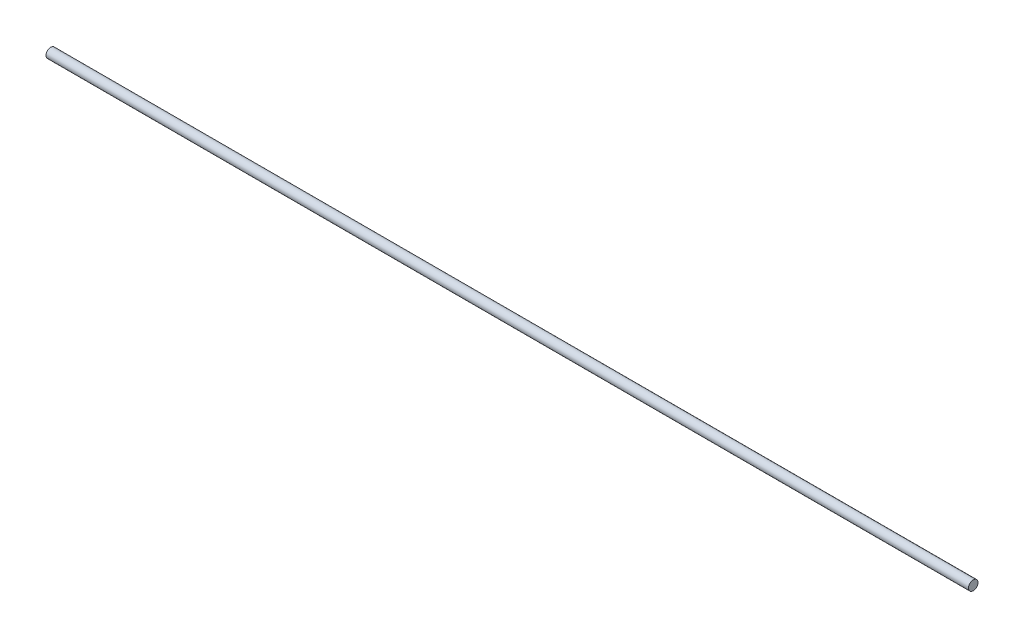
SolidWorks part; units mm, degrees
material "Alloy Steel"
ref_plane "Front Plane" through (0, 0, 0) normal (0, 0, 1) x (1, 0, 0)
ref_plane "Top Plane" through (0, 0, 0) normal (0, 1, 0) x (1, 0, 0)
ref_plane "Right Plane" through (0, 0, 0) normal (1, 0, 0) x (0, 0, -1)
sketch "Sketch1" plane through (0, 0, 0) normal (1, 0, 0) x (0, 0, -1)
  circle A0 centre (0, 0) radius 3.15
  dimension "D1" = 6.3
extrude "Boss-Extrude1" add sketch "Sketch1" along normal mid plane 613
